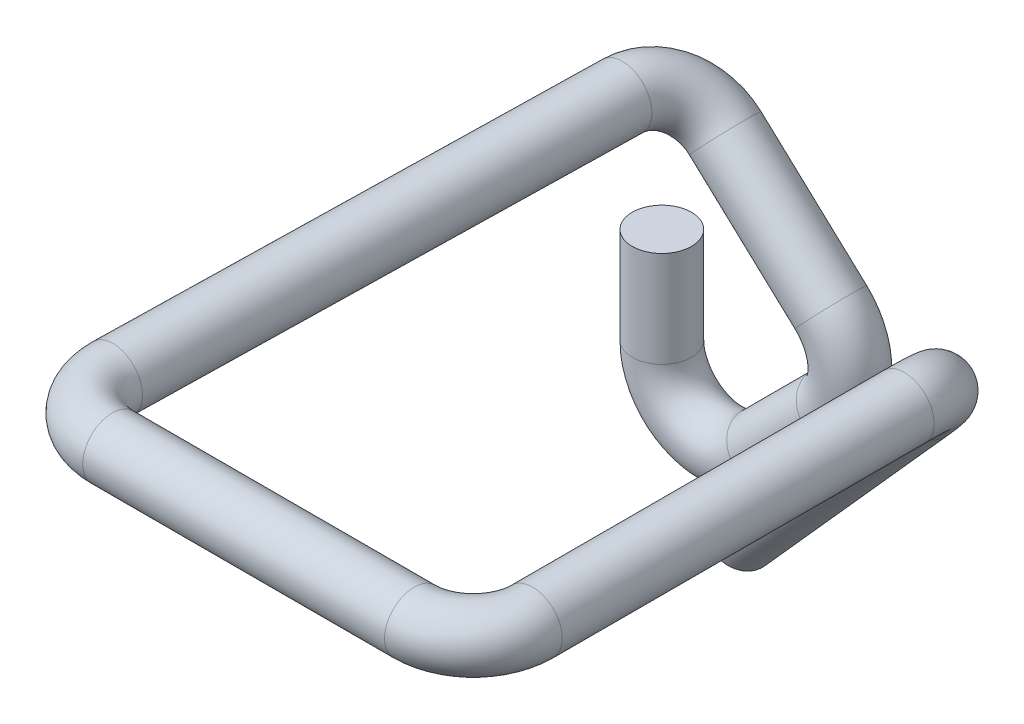
SolidWorks part; units mm, degrees
ref_plane "Front Plane" through (0, 0, 0) normal (0, 0, 1) x (1, 0, 0)
ref_plane "Top Plane" through (0, 0, 0) normal (0, 1, 0) x (1, 0, 0)
ref_plane "Right Plane" through (0, 0, 0) normal (1, 0, 0) x (0, 0, -1)
sketch3d "3DSketch1"
  line L0 (0, 30.6605, 0) -> (0, 51.2516, 0)
  line L1 (21.6803, 21.6803, 0) -> (36.593, 36.593, 0)
  line L2 (45.9238, 45.9238, 0) -> (4.4184, 45.9238, 0) construction
  line L3 (4.4184, 45.9238, 0) -> (4.4184, 84.3672, 0) construction
  line L4 (13.5951, 75.8675, 0) -> (36.2428, 54.8907, 0)
  line L5 (4.1591, 84.3672, 12.5056) -> (1.9401, 84.3672, 119.4943)
  line L6 (14.6374, 84.3672, 132.4577) -> (79.353, 84.3672, 132.4577)
  line L7 (92.053, 84.3672, 119.7577) -> (92.053, 84.3672, 40.0423)
  line L8 (92.053, 84.3672, 27.3423) -> (92.053, 30.8878, 27.3423) construction
  line L9 (92.053, 30.8878, 27.3423) -> (44.2167, 30.8878, 27.3423) construction
  line L10 (44.2167, 30.8878, 27.3423) -> (83.5861, 74.9014, 27.3423)
  arc A0 (83.5861, 74.9014, 27.3423) -> (92.053, 84.3672, 40.0423) centre (83.5861, 74.9014, 40.0423) ccw
  arc A1 (14.6374, 84.3672, 132.4577) -> (1.9401, 84.3672, 119.4943) centre (14.6374, 84.3672, 119.7577) ccw
  arc A2 (4.1591, 84.3672, 12.5056) -> (13.5951, 75.8675, 0) centre (13.4735, 75.7362, 12.6987) ccw
  arc A3 (36.2428, 54.8907, 0) -> (36.593, 36.593, 0) centre (27.6128, 45.5733, 0) ccw
  arc A4 (21.6803, 21.6803, 0) -> (0, 30.6605, 0) centre (12.7, 30.6605, 0) ccw
  arc A5 (92.053, 84.3672, 119.7577) -> (79.353, 84.3672, 132.4577) centre (79.353, 84.3672, 119.7577) ccw
  point P6 (25.1711, 45.9238, 0)
  point P14 (92.053, 84.3672, 27.3423)
  point P16 (93.0519, 66.4345, 40.0423)
  point P19 (1.6713, 84.3672, 132.4577)
  point P20 (14.6374, 71.6672, 119.7577)
  point P23 (4.4184, 84.3672, 0)
  point P25 (4.8444, 66.4198, 12.5198)
  point P28 (45.9238, 45.9238, 0)
  point P30 (27.6128, 45.5733, -12.7)
  point P33 (0, 0, 0)
  point P34 (12.7, 30.6605, -12.7)
  point P37 (92.053, 84.3672, 132.4577)
  point P38 (79.353, 71.6672, 119.7577)
  dimension "D1" = 12.7
  dimension "D2" = 12.7
sweep "Sweep1" add path "3DSketch1" circular profile diameter 12.7 parameters "D3"=12.7
